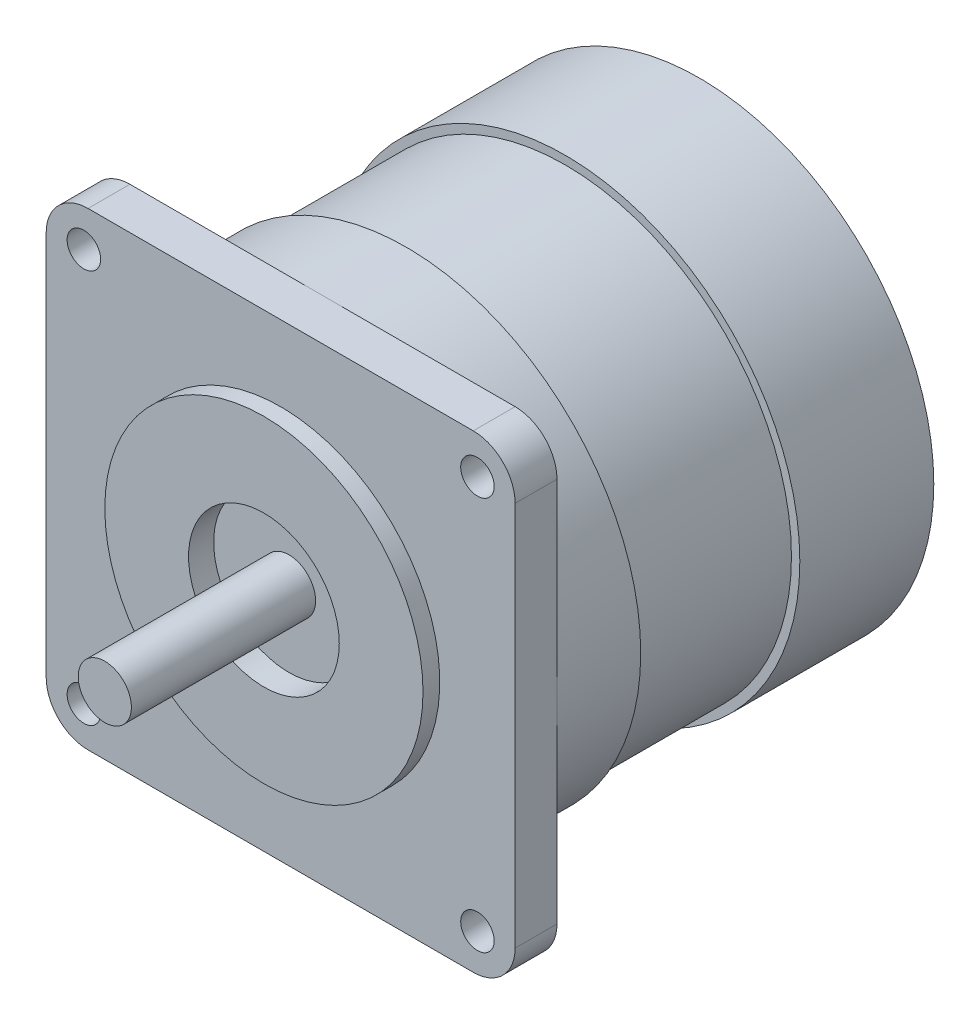
SolidWorks part; units mm, degrees
ref_plane "Plan de face" through (0, 0, 0) normal (0, 0, 1) x (1, 0, 0)
ref_plane "Plan de dessus" through (0, 0, 0) normal (0, 1, 0) x (1, 0, 0)
ref_plane "Plan de droite" through (0, 0, 0) normal (1, 0, 0) x (0, 0, -1)
sketch "Esquisse1" plane through (0, 0, 0) normal (0, 0, 1) x (1, 0, 0)
  line L0 (0, -28) -> (0, 28) construction
  line L1 (-28, -28) -> (28, -28)
  line L2 (-28, -28) -> (-28, 28)
  line L3 (-28, 28) -> (28, 28)
  line L4 (28, -28) -> (28, 28)
  line L5 (-28, 0) -> (28, 0) construction
  dimension "D1" = 56
  dimension "D2" = 56
extrude "Boss.-Extru.1" add sketch "Esquisse1" along normal blind 5
sketch "Esquisse2" plane through (0, 0, 0) normal (0, 1, 0) x (1, 0, 0)
  line L0 (0, 0) -> (0, 45) construction
  line L1 (0, 0) -> (28, 0)
  line L2 (28, 0) -> (28, 10)
  line L3 (28, 10) -> (27, 10)
  line L4 (27, 10) -> (27, 29)
  line L5 (27, 29) -> (28, 29)
  line L6 (28, 29) -> (28, 45)
  line L7 (28, 45) -> (0, 45)
  line L8 (0, 45) -> (0, 0)
  dimension "D1" = 45
  dimension "D2" = 16
  dimension "D3" = 10
  dimension "D4" = 27
revolve "Révolution1" add sketch "Esquisse2" angle 360 about L0
sketch "Esquisse3" plane through (0, 0, 5) normal (0, 0, 1) x (1, 0, 0)
  circle A0 centre (0, 0) radius 19
  dimension "D1" = 38
extrude "Boss.-Extru.2" add sketch "Esquisse3" along normal blind 2
sketch "Esquisse4" plane through (0, 0, 7) normal (0, 0, 1) x (1, 0, 0)
  circle A0 centre (0, 0) radius 9
  dimension "D1" = 18
extrude "Enlèv. mat.-Extru.1" cut sketch "Esquisse4" against normal blind 3
sketch "Esquisse5" plane through (0, 0, 4) normal (0, 0, 1) x (1, 0, 0)
  circle A0 centre (0, 0) radius 3.175
  dimension "D1" = 6.35
extrude "Boss.-Extru.3" add sketch "Esquisse5" along normal blind 22
sketch "Esquisse6" plane through (0, 0, 5) normal (0, 0, 1) x (1, 0, 0)
  line L0 (0, 28) -> (0, 0) construction
  line L1 (28, 28) -> (-28, 28) construction
  line L2 (0, 0) -> (28, 0) construction
  line L3 (28, -28) -> (28, 28) construction
  circle A0 centre (23.5, 23.5) radius 2
  circle A1 centre (-23.5, 23.5) radius 2
  circle A2 centre (23.5, -23.5) radius 2
  circle A3 centre (-23.5, -23.5) radius 2
  dimension "D1" = 4
  dimension "D2" = 23.5
  dimension "D3" = 23.5
extrude "Enlèv. mat.-Extru.2" cut sketch "Esquisse6" against normal up to next
fillet "Congé1" radius 5 4 edges at (-28, -28, 2.5) (28, -28, 2.5) (28, 28, 2.5) (-28, 28, 2.5)
